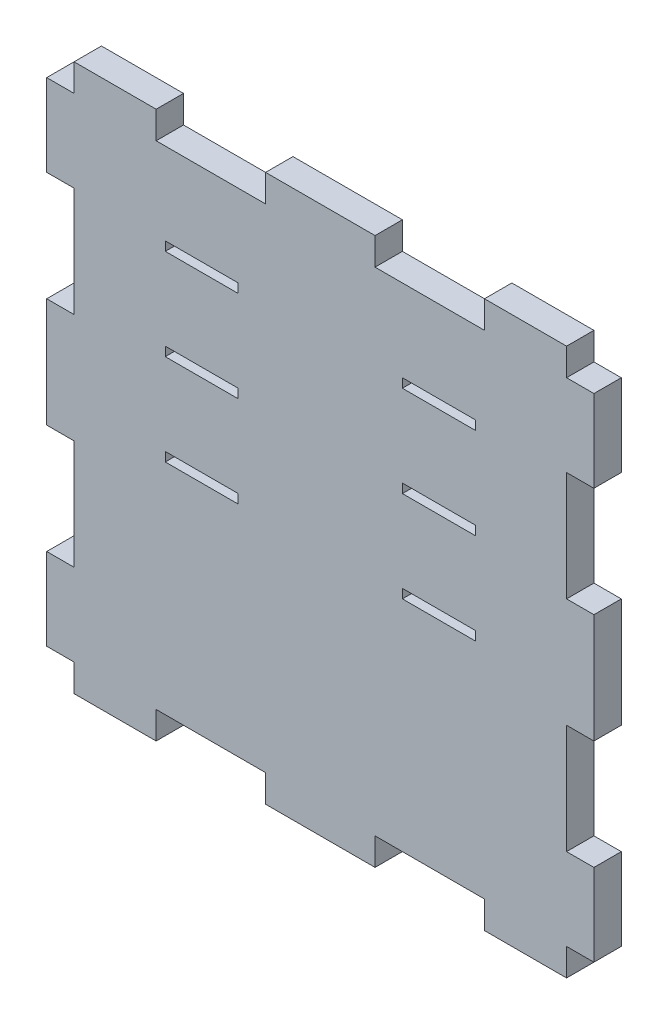
SolidWorks part; units mm, degrees
ref_plane "Front Plane" through (0, 0, 0) normal (0, 0, 1) x (1, 0, 0)
ref_plane "Top Plane" through (0, 0, 0) normal (0, 1, 0) x (1, 0, 0)
ref_plane "Right Plane" through (0, 0, 0) normal (1, 0, 0) x (0, 0, -1)
sketch "Sketch1" plane through (0, 0, 0) normal (0, 0, 1) x (1, 0, 0)
  line L1 (-69.1598, 27.7467) -> (121.3402, 27.7467)
  line L2 (-69.1598, 27.7467) -> (-69.1598, -162.7533)
  line L3 (-69.1598, -162.7533) -> (121.3402, -162.7533)
  line L4 (121.3402, 27.7467) -> (121.3402, -162.7533)
  dimension "D1" = 190.5
  dimension "D2" = 190.5
extrude "Boss-Extrude2" add sketch "Sketch1" along normal blind 9.525
sketch "Sketch2" plane through (0, 0, 9.525) normal (0, 0, 1) x (1, 0, 0)
  line L0 (121.3402, 27.7467) -> (-69.1598, 27.7467) construction
  line L1 (-31.0598, 27.7467) -> (7.0402, 27.7467)
  line L2 (-31.0598, 27.7467) -> (-31.0598, 18.2217)
  line L3 (-31.0598, 18.2217) -> (7.0402, 18.2217)
  line L4 (7.0402, 27.7467) -> (7.0402, 18.2217)
  dimension "D1" = 38.1
  dimension "D2" = 38.1
  dimension "D3" = 9.525
extrude "Cut-Extrude1" cut sketch "Sketch2" against normal blind 9.525
sketch "Sketch3" plane through (0, 0, 9.525) normal (0, 0, 1) x (1, 0, 0)
  line L0 (121.3402, 27.7467) -> (7.0402, 27.7467) construction
  line L1 (45.1402, 27.7467) -> (83.2402, 27.7467)
  line L2 (45.1402, 27.7467) -> (45.1402, 18.2217)
  line L3 (45.1402, 18.2217) -> (83.2402, 18.2217)
  line L4 (83.2402, 27.7467) -> (83.2402, 18.2217)
  dimension "D1" = 38.1
  dimension "D2" = 38.1
  dimension "D3" = 9.525
extrude "Cut-Extrude2" cut sketch "Sketch3" against normal blind 9.525
sketch "Sketch4" plane through (0, 0, 9.525) normal (0, 0, 1) x (1, 0, 0)
  line L0 (121.3402, -162.7533) -> (121.3402, 27.7467) construction
  line L1 (121.3402, -10.3533) -> (111.8152, -10.3533)
  line L2 (121.3402, -10.3533) -> (121.3402, -48.4533)
  line L3 (121.3402, -48.4533) -> (111.8152, -48.4533)
  line L4 (111.8152, -10.3533) -> (111.8152, -48.4533)
  dimension "D1" = 38.1
  dimension "D2" = 9.525
  dimension "D3" = 38.1
extrude "Cut-Extrude3" cut sketch "Sketch4" against normal blind 9.525
sketch "Sketch5" plane through (0, 0, 9.525) normal (0, 0, 1) x (1, 0, 0)
  line L0 (121.3402, -162.7533) -> (121.3402, -48.4533) construction
  line L1 (121.3402, -86.5533) -> (111.8152, -86.5533)
  line L2 (121.3402, -86.5533) -> (121.3402, -124.6533)
  line L3 (121.3402, -124.6533) -> (111.8152, -124.6533)
  line L4 (111.8152, -86.5533) -> (111.8152, -124.6533)
  dimension "D1" = 9.525
  dimension "D2" = 38.1
  dimension "D3" = 38.1
extrude "Cut-Extrude4" cut sketch "Sketch5" against normal blind 9.525
sketch "Sketch6" plane through (0, 0, 9.525) normal (0, 0, 1) x (1, 0, 0)
  line L0 (-69.1598, -162.7533) -> (121.3402, -162.7533) construction
  line L1 (83.2402, -162.7533) -> (45.1402, -162.7533)
  line L2 (83.2402, -162.7533) -> (83.2402, -153.2283)
  line L3 (83.2402, -153.2283) -> (45.1402, -153.2283)
  line L4 (45.1402, -162.7533) -> (45.1402, -153.2283)
  dimension "D1" = 9.525
  dimension "D2" = 38.1
  dimension "D3" = 38.1
extrude "Cut-Extrude5" cut sketch "Sketch6" against normal blind 9.525
sketch "Sketch7" plane through (0, 0, 9.525) normal (0, 0, 1) x (1, 0, 0)
  line L0 (-69.1598, -162.7533) -> (45.1402, -162.7533) construction
  line L1 (7.0402, -162.7533) -> (-31.0598, -162.7533)
  line L2 (7.0402, -162.7533) -> (7.0402, -153.2283)
  line L3 (7.0402, -153.2283) -> (-31.0598, -153.2283)
  line L4 (-31.0598, -162.7533) -> (-31.0598, -153.2283)
  dimension "D1" = 38.1
  dimension "D2" = 9.525
  dimension "D3" = 38.1
extrude "Cut-Extrude6" cut sketch "Sketch7" against normal blind 9.525
sketch "Sketch8" plane through (0, 0, 9.525) normal (0, 0, 1) x (1, 0, 0)
  line L0 (-69.1598, 27.7467) -> (-69.1598, -162.7533) construction
  line L1 (-69.1598, -124.6533) -> (-59.6348, -124.6533)
  line L2 (-69.1598, -124.6533) -> (-69.1598, -86.5533)
  line L3 (-69.1598, -86.5533) -> (-59.6348, -86.5533)
  line L4 (-59.6348, -124.6533) -> (-59.6348, -86.5533)
  dimension "D1" = 38.1
  dimension "D2" = 38.1
  dimension "D3" = 9.525
extrude "Cut-Extrude7" cut sketch "Sketch8" against normal blind 9.525
sketch "Sketch9" plane through (0, 0, 9.525) normal (0, 0, 1) x (1, 0, 0)
  line L0 (-69.1598, 27.7467) -> (-69.1598, -86.5533) construction
  line L1 (-69.1598, -48.4533) -> (-59.6348, -48.4533)
  line L2 (-69.1598, -48.4533) -> (-69.1598, -10.3533)
  line L3 (-69.1598, -10.3533) -> (-59.6348, -10.3533)
  line L4 (-59.6348, -48.4533) -> (-59.6348, -10.3533)
  dimension "D1" = 9.525
  dimension "D2" = 38.1
  dimension "D3" = 38.1
extrude "Cut-Extrude8" cut sketch "Sketch9" against normal blind 9.525
sketch "Sketch10" plane through (0, 0, 9.525) normal (0, 0, 1) x (1, 0, 0)
  line L0 (-69.1598, -162.7533) -> (-31.0598, -162.7533) construction
  line L1 (-59.6348, -162.7533) -> (-69.1598, -162.7533)
  line L2 (-59.6348, -162.7533) -> (-59.6348, -153.2283)
  line L3 (-59.6348, -153.2283) -> (-69.1598, -153.2283)
  line L4 (-69.1598, -162.7533) -> (-69.1598, -153.2283)
  line L5 (-69.1598, -124.6533) -> (-69.1598, -162.7533) construction
  dimension "D1" = 9.525
  dimension "D2" = 9.525
extrude "Cut-Extrude9" cut sketch "Sketch10" against normal blind 9.525
sketch "Sketch11" plane through (0, 0, 9.525) normal (0, 0, 1) x (1, 0, 0)
  line L0 (-69.1598, 27.7467) -> (-69.1598, -10.3533) construction
  line L1 (-69.1598, 18.2217) -> (-59.6348, 18.2217)
  line L2 (-69.1598, 18.2217) -> (-69.1598, 27.7467)
  line L3 (-69.1598, 27.7467) -> (-59.6348, 27.7467)
  line L4 (-59.6348, 18.2217) -> (-59.6348, 27.7467)
  line L5 (-31.0598, 27.7467) -> (-69.1598, 27.7467) construction
extrude "Cut-Extrude10" cut sketch "Sketch11" against normal blind 9.525
sketch "Sketch12" plane through (0, 0, 9.525) normal (0, 0, 1) x (1, 0, 0)
  line L0 (121.3402, 27.7467) -> (83.2402, 27.7467) construction
  line L1 (111.8152, 27.7467) -> (121.3402, 27.7467)
  line L2 (111.8152, 27.7467) -> (111.8152, 18.2217)
  line L3 (111.8152, 18.2217) -> (121.3402, 18.2217)
  line L4 (121.3402, 27.7467) -> (121.3402, 18.2217)
  line L5 (121.3402, -10.3533) -> (121.3402, 27.7467) construction
  dimension "D1" = 9.525
  dimension "D2" = 9.525
extrude "Cut-Extrude11" cut sketch "Sketch12" against normal blind 9.525
sketch "Sketch13" plane through (0, 0, 9.525) normal (0, 0, 1) x (1, 0, 0)
  line L0 (83.2402, -162.7533) -> (121.3402, -162.7533) construction
  line L1 (111.8152, -162.7533) -> (121.3402, -162.7533)
  line L2 (111.8152, -162.7533) -> (111.8152, -153.2283)
  line L3 (111.8152, -153.2283) -> (121.3402, -153.2283)
  line L4 (121.3402, -162.7533) -> (121.3402, -153.2283)
  line L5 (121.3402, -162.7533) -> (121.3402, -124.6533) construction
  dimension "D1" = 9.525
  dimension "D2" = 9.525
extrude "Cut-Extrude12" cut sketch "Sketch13" against normal blind 9.525
sketch "Sketch14" plane through (0, 0, 9.525) normal (0, 0, 1) x (1, 0, 0)
  line L1 (80.0652, -10.3533) -> (54.6652, -10.3533)
  line L2 (80.0652, -10.3533) -> (80.0652, -13.5283)
  line L3 (80.0652, -13.5283) -> (54.6652, -13.5283)
  line L4 (54.6652, -10.3533) -> (54.6652, -13.5283)
  line L7 (-2.4848, -10.3533) -> (-27.8848, -10.3533)
  line L8 (-2.4848, -10.3533) -> (-2.4848, -13.5283)
  line L9 (-2.4848, -13.5283) -> (-27.8848, -13.5283)
  line L10 (-27.8848, -10.3533) -> (-27.8848, -13.5283)
  line L18 (111.8152, -10.3533) -> (111.8152, -48.4533) construction
  line L20 (-31.0598, 18.2217) -> (7.0402, 18.2217) construction
  line L21 (45.1402, 18.2217) -> (83.2402, 18.2217) construction
  line L22 (-59.6348, -48.4533) -> (-59.6348, -10.3533) construction
  line L23 (80.0652, -42.1033) -> (54.6652, -42.1033)
  line L24 (80.0652, -42.1033) -> (80.0652, -45.2783)
  line L25 (80.0652, -45.2783) -> (54.6652, -45.2783)
  line L26 (54.6652, -42.1033) -> (54.6652, -45.2783)
  line L27 (-2.4848, -42.1033) -> (-27.8848, -42.1033)
  line L28 (-2.4848, -42.1033) -> (-2.4848, -45.2783)
  line L29 (-2.4848, -45.2783) -> (-27.8848, -45.2783)
  line L30 (-27.8848, -42.1033) -> (-27.8848, -45.2783)
  line L31 (111.8152, -86.5533) -> (111.8152, -124.6533) construction
  line L32 (80.0652, -73.8533) -> (54.6652, -73.8533)
  line L33 (80.0652, -73.8533) -> (80.0652, -77.0283)
  line L34 (80.0652, -77.0283) -> (54.6652, -77.0283)
  line L35 (54.6652, -73.8533) -> (54.6652, -77.0283)
  line L36 (-59.6348, -124.6533) -> (-59.6348, -86.5533) construction
  line L37 (-2.4848, -73.8533) -> (-27.8848, -73.8533)
  line L38 (-2.4848, -73.8533) -> (-2.4848, -77.0283)
  line L39 (-2.4848, -77.0283) -> (-27.8848, -77.0283)
  line L40 (-27.8848, -73.8533) -> (-27.8848, -77.0283)
  dimension "D1" = 31.75
  dimension "D2" = 25.4
  dimension "D3" = 3.175
  dimension "D4" = 57.15
  dimension "D5" = 25.4
  dimension "D6" = 3.175
  dimension "D7" = 28.575
  dimension "D8" = 28.575
  dimension "D9" = 25.4
  dimension "D10" = 3.175
  dimension "D11" = 28.575
  dimension "D12" = 3.175
  dimension "D13" = 28.575
  dimension "D14" = 25.4
  dimension "D15" = 31.75
  dimension "D16" = 31.75
  dimension "D17" = 28.575
  dimension "D18" = 3.175
  dimension "D19" = 25.4
  dimension "D20" = 31.75
  dimension "D21" = 3.175
  dimension "D22" = 25.4
  dimension "D23" = 28.575
  dimension "D24" = 31.75
extrude "Cut-Extrude13" cut sketch "Sketch14" against normal through all
